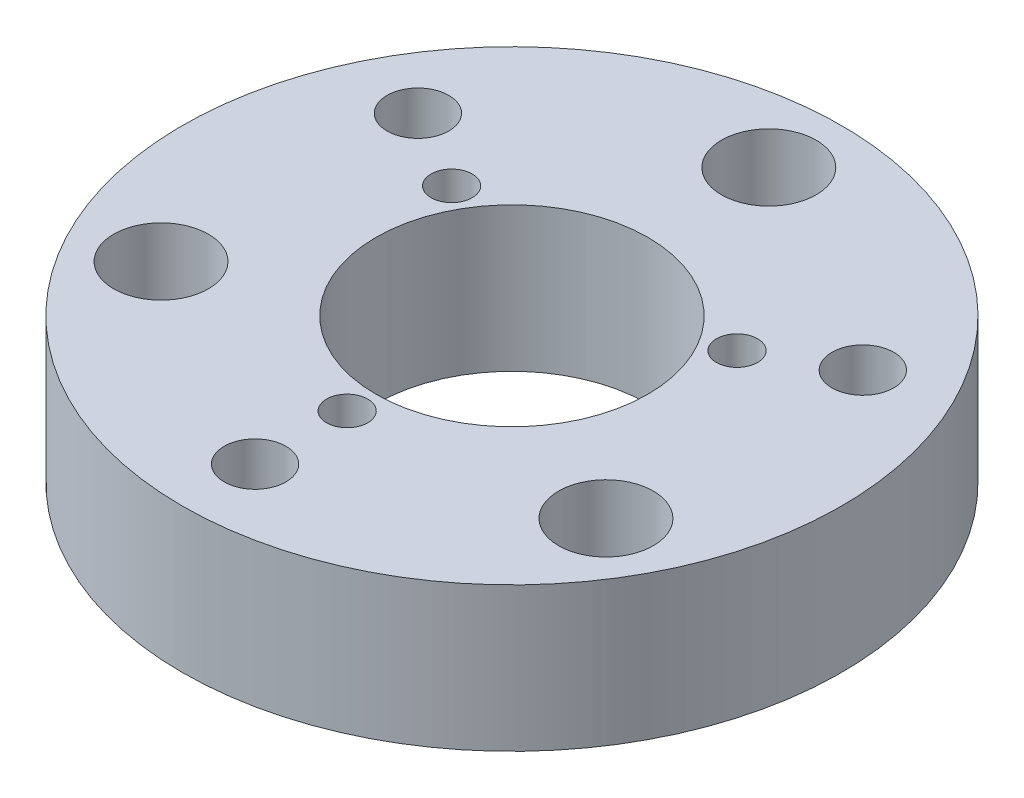
SolidWorks part; units mm, degrees
ref_plane "前视基准面" through (0, 0, 0) normal (0, 0, 1) x (1, 0, 0)
ref_plane "上视基准面" through (0, 0, 0) normal (0, 1, 0) x (1, 0, 0)
ref_plane "右视基准面" through (0, 0, 0) normal (1, 0, 0) x (0, 0, -1)
sketch "草图1" plane through (0, 0, 0) normal (0, 1, 0) x (1, 0, 0)
  line L0 (0, 0) -> (-10.8, -18.7061) construction
  line L1 (-10.8, -18.7061) -> (10.8, -18.7061) construction
  line L2 (10.8, -18.7061) -> (0, 0) construction
  line L3 (-10.8, -18.7061) -> (5.4, -9.3531) construction
  line L4 (10.8, -18.7061) -> (-5.4, -9.3531) construction
  circle A0 centre (0, -12.4708) radius 16
  circle A1 centre (0, -12.4708) radius 6.6
  circle A2 centre (-10.8, -18.7061) radius 1.3
  circle A3 centre (10.8, -18.7061) radius 1.3
  circle A4 centre (0, 0) radius 1.3
  dimension "D4" = 32
  dimension "D5" = 13.2
  dimension "D6" = 2.6
  dimension "D7" = 2.6
  dimension "D8" = 2.6
  dimension "D1" = 21.6
  dimension "D2" = 21.6
  dimension "D3" = 21.6
extrude "凸台-拉伸1" add sketch "草图1" along normal blind 7
sketch "草图2" plane through (0, 7, 0) normal (0, 1, 0) x (1, 0, 0)
  circle A0 centre (-10.8, -18.7061) radius 2.3
  circle A1 centre (10.8, -18.7061) radius 2.3
  circle A2 centre (0, 0) radius 2.3
  dimension "D1" = 4.6
  dimension "D2" = 4.6
  dimension "D3" = 4.6
extrude "切除-拉伸2" cut sketch "草图2" against normal blind 5
sketch "草图4" plane through (0, 7, 0) normal (0, 1, 0) x (1, 0, 0)
  line L0 (0, 0) -> (-10.8, -18.7061) construction
  line L1 (0, -12.4708) -> (-13.8564, -4.4708) construction
  line L2 (0, -2.4708) -> (0, -22.4708) construction
  circle A1 centre (0, -12.4708) radius 16 construction
  circle A2 centre (-6.9282, -8.4708) radius 1
  circle A3 centre (6.9282, -8.4708) radius 1
  circle A4 centre (0, -20.4708) radius 1
  dimension "D3" = 2
  dimension "D5" = 2
  dimension "D2" = 8
  dimension "D4" = 8
extrude "切除-拉伸3" cut sketch "草图4" against normal blind 2
sketch "草图5" plane through (0, 7, 0) normal (0, 1, 0) x (1, 0, 0)
  line L0 (0, -12.4708) -> (-6.9282, -8.4708) construction
  line L1 (-6.9282, -8.4708) -> (-13.8564, -4.4708) construction
  line L2 (0, -12.4708) -> (6.9282, -8.4708) construction
  line L3 (6.9282, -8.4708) -> (13.8564, -4.4708) construction
  line L4 (0, -12.4708) -> (0, -20.4708) construction
  line L5 (0, -20.4708) -> (0, -28.4708) construction
  circle A0 centre (0, -12.4708) radius 16 construction
  circle A1 centre (0, -12.4708) radius 12.4708 construction
  circle A2 centre (-10.8, -6.2354) radius 1.5
  circle A3 centre (10.8, -6.2354) radius 1.5
  circle A4 centre (0, -24.9415) radius 1.5
  dimension "D1" = 3
  dimension "D2" = 3
  dimension "D3" = 3
extrude "切除-拉伸4" cut sketch "草图5" against normal through all
sketch "草图6" plane through (0, 0, 0) normal (0, -1, 0) x (1, 0, 0)
  circle A0 centre (0, 24.9415) radius 2.65
  circle A1 centre (-10.8, 6.2354) radius 2.65
  circle A2 centre (10.8, 6.2354) radius 2.65
  dimension "D1" = 5.3
  dimension "D2" = 5.3
  dimension "D3" = 5.3
extrude "切除-拉伸5" cut sketch "草图6" against normal blind 4
